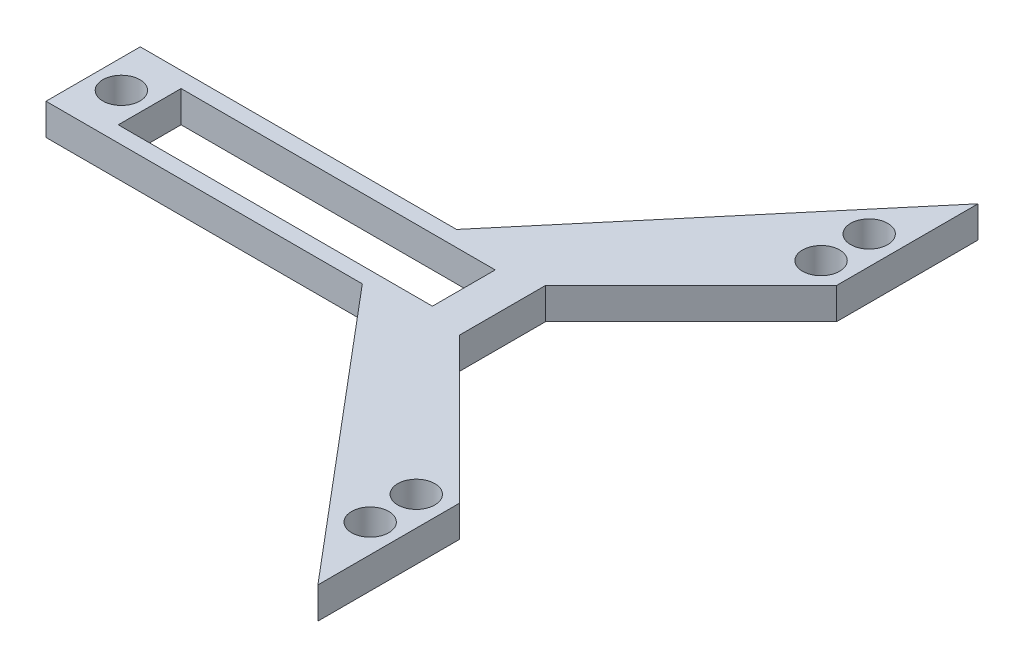
SolidWorks part; units mm, degrees
ref_plane "Front Plane" through (0, 0, 0) normal (0, 0, 1) x (1, 0, 0)
ref_plane "Top Plane" through (0, 0, 0) normal (0, 1, 0) x (1, 0, 0)
ref_plane "Right Plane" through (0, 0, 0) normal (1, 0, 0) x (0, 0, -1)
sketch "Sketch1" plane through (0, 0, 0) normal (0, 1, 0) x (1, 0, 0)
  line L0 (3.2219, 6.0298) -> (14.9883, 17.7962)
  line L1 (0, 0) -> (-25.2984, 0)
  line L2 (0, 0) -> (0, 5.08)
  line L3 (0, 5.08) -> (-25.2984, 5.08)
  line L4 (-25.2984, 0) -> (-25.2984, 5.08)
  line L9 (-4.2958, -1.27) -> (-29.8704, -1.27)
  line L10 (3.2219, -0.9498) -> (3.2219, 6.0298)
  line L11 (-4.2958, 6.35) -> (-29.8704, 6.35)
  line L12 (-29.8704, -1.27) -> (-29.8704, 6.35)
  line L13 (3.2219, -0.9498) -> (-29.8704, 6.35) construction
  line L14 (3.1479, 6.0134) -> (-29.8704, -1.27) construction
  line L15 (-55, 0) -> (55, 0) construction
  line L16 (-4.2958, 6.35) -> (14.9883, 29.2262)
  line L17 (14.9883, 29.2262) -> (14.9883, 17.7962)
  line L18 (-5.3349, 2.54) -> (11.7786, 2.54) construction
  line L19 (3.2219, -0.9498) -> (14.9883, -12.7162)
  line L20 (14.9883, -24.1462) -> (14.9883, -12.7162)
  line L21 (-4.2958, -1.27) -> (14.9883, -24.1462)
  circle A0 centre (-27.5844, 2.54) radius 1.4986
  circle A1 centre (12.9563, 23.6382) radius 1.4986
  circle A2 centre (12.9563, 19.8282) radius 1.4986
  circle A3 centre (12.9563, -14.7482) radius 1.4986
  circle A4 centre (12.9563, -18.5582) radius 1.4986
  point P6 (-12.5984, 2.54)
  point P19 (3.2219, 2.54)
  point P32 (0, 0)
  point P33 (0, 0)
  point P34 (0, 0)
  dimension "D11" = 2.9972
  dimension "D16" = 2.9972
  dimension "D1" = 25.2984
  dimension "D2" = 5.08
  dimension "D3" = 7.62
  dimension "D4" = 1.27
  dimension "D5" = 33.02
  dimension "D6" = 4.572
  dimension "D7" = 45
  dimension "D8" = 11.43
  dimension "D9" = 19.2841
  dimension "D10" = 25.5746
  dimension "D12" = 2.286
  dimension "D13" = 3.81
  dimension "D14" = 6.9795
  dimension "D15" = 16.6402
  dimension "D17" = 5.588
  dimension "D18" = 2.032
  dimension "D19" = 2.032
  dimension "D20" = 3.81
extrude "Boss-Extrude2" add sketch "Sketch1" along normal blind 2.54 contours L20 L19 L10 L0 L17 L16 L11 L12 L9 L21
sketch "Sketch7" plane through (0, 2.54, 0) normal (0, 1, 0) x (1, 0, 0)
  line L0 (-29.8704, -1.27) -> (-29.8704, 6.35) construction
  line L1 (-4.2958, 6.35) -> (-29.8704, 6.35) construction
  line L2 (14.9883, 29.2262) -> (14.9883, 17.7962) construction
  line L3 (-2.3486, 2.54) -> (7.8486, 2.54) construction
  line L5 (0.1016, 5.08) -> (-25.2984, 5.08)
  line L6 (0.1016, 5.08) -> (0.1016, 0)
  line L7 (0.1016, 0) -> (-25.2984, 0)
  line L8 (-25.2984, 5.08) -> (-25.2984, 0)
  line L9 (0.1016, 5.08) -> (-25.2984, 0) construction
  line L10 (0.1016, 0) -> (-25.2984, 5.08) construction
  line L11 (-4.2958, -1.27) -> (-29.8704, -1.27) construction
  circle A0 centre (-27.5844, 2.54) radius 1.4986
  circle A1 centre (12.7023, 22.7133) radius 1.4986
  circle A2 centre (12.622, 18.9042) radius 1.4986
  circle A3 centre (12.622, -13.8242) radius 1.4986
  circle A4 centre (12.7023, -17.6333) radius 1.4986
  point P19 (-12.5984, 2.54)
  dimension "D1" = 2.9972
  dimension "D6" = 2.9972
  dimension "D8" = 2.3662
  dimension "D2" = 2.286
  dimension "D3" = 3.81
  dimension "D4" = 2.286
  dimension "D5" = 6.5129
  dimension "D7" = 3.81
  dimension "D9" = 4.572
  dimension "D10" = 25.4
  dimension "D11" = 1.27
  dimension "D12" = 5.08
extrude "Cut-Extrude1" cut sketch "Sketch7" against normal blind 2.54
